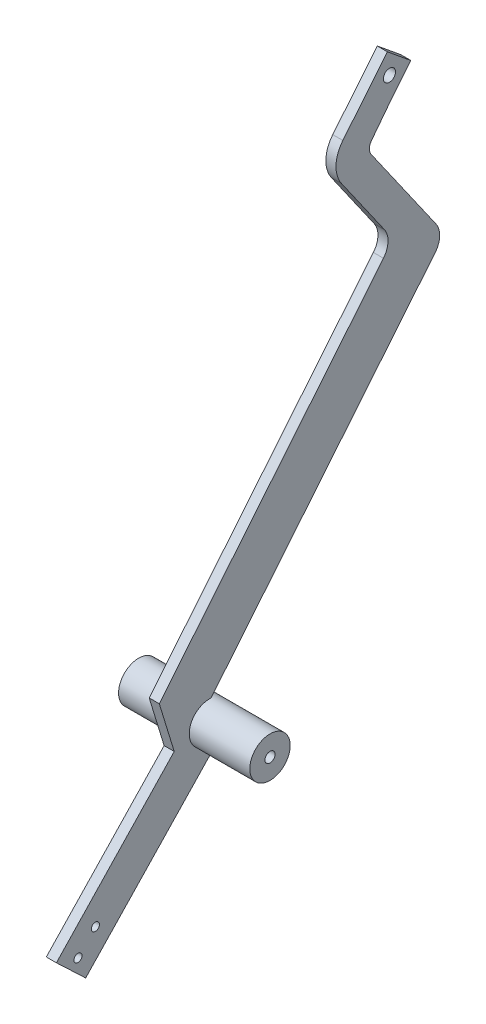
SolidWorks part; units mm, degrees
ref_plane "Front Plane" through (0, 0, 0) normal (0, 0, 1) x (1, 0, 0)
ref_plane "Top Plane" through (0, 0, 0) normal (0, 1, 0) x (1, 0, 0)
ref_plane "Right Plane" through (0, 0, 0) normal (1, 0, 0) x (0, 0, -1)
ref_plane "Plane1" through (-60.9982, 1573.0605, 105.0668) normal (1, 0, 0) x (0, 0.7736, -0.6337)
sketch "Sketch3" plane through (-60.9982, 1573.0605, 105.0668) normal (1, 0, 0) x (0, 0.7736, -0.6337)
  circle A0 centre (-394.0453, 76.3488) radius 20
  circle A1 centre (-394.0453, 76.3488) radius 5
  dimension "D1" = 40
extrude "Boss-Extrude1" add sketch "Sketch3" along normal mid plane 130
sketch "Sketch5" plane through (-60.9982, 1573.0605, 105.0668) normal (1, 0, 0) x (0, 0.7736, -0.6337)
  line L0 (-392.5842, 96.2954) -> (-591.1232, 110.8378)
  line L1 (-594.0453, 45) -> (-594.0453, 153.138) construction
  line L2 (-395.5063, 56.4022) -> (-594.0453, 70.9447)
  line L3 (-594.0453, 70.9447) -> (-591.1232, 110.8378)
  line L5 (-592.5842, 90.8913) -> (-530.6321, 86.3534) construction
  arc A0 (-392.5842, 96.2954) -> (-395.5063, 56.4022) centre (-394.0453, 76.3488) ccw
  circle A1 centre (-394.0453, 76.3488) radius 20 construction
  circle A2 centre (-582.611, 90.1608) radius 4
  circle A3 centre (-557.6778, 88.3345) radius 4
  dimension "D2" = 8
  dimension "D3" = 8
  dimension "D1" = 40
  dimension "D4" = 10
  dimension "25" = 25
extrude "Boss-Extrude2" add sketch "Sketch5" along normal mid plane 10
sketch "Sketch6" plane through (-60.9982, 1573.0605, 105.0668) normal (1, 0, 0) x (0, 0.7736, -0.6337)
  line L0 (6.218, 39.6467) -> (6.218, 202.9451) construction
  line L1 (-377.6198, 87.7595) -> (-27.2929, 87.7595)
  line L2 (-394.0453, 140.5353) -> (-43.6088, 140.5353)
  line L3 (79.2927, 22.8774) -> (79.2927, 371.7765) construction
  line L4 (64.3447, 37.2601) -> (64.3447, 317.7365) construction
  line L5 (-8.0405, 102.3427) -> (22.3027, 210.1879)
  line L6 (64.136, 218.4616) -> (94.3447, 218.4616)
  line L7 (64.3447, 248.4616) -> (94.3447, 248.4616)
  line L8 (94.3447, 218.4616) -> (94.3447, 248.4616)
  line L9 (64.136, 218.4616) -> (94.3447, 248.4616) construction
  line L10 (64.3447, 248.4616) -> (94.3447, 218.4616) construction
  line L11 (-24.3564, 155.1184) -> (-4.2481, 226.5869)
  line L12 (64.3447, 248.4616) -> (24.6306, 248.4616)
  line L13 (64.136, 218.4616) -> (31.6256, 217.4749)
  line L14 (-394.0453, 140.5353) -> (-422.0571, 98.4542)
  line L16 (-422.0571, 98.4542) -> (-387.3077, 95.1798)
  line L17 (-392.5842, 96.2954) -> (-591.1232, 110.8378) construction
  line L20 (74.2929, 233.5648) -> (84.2924, 233.4625) construction
  circle A0 centre (79.2927, 233.5136) radius 6
  arc A1 (31.6256, 217.4749) -> (22.3027, 210.1879) centre (31.929, 207.4795) ccw
  arc A2 (-4.2481, 226.5869) -> (24.6306, 248.4616) centre (24.6306, 218.4616) cw
  arc A3 (-43.6088, 140.5353) -> (-24.3564, 155.1184) centre (-43.6088, 160.5353) ccw
  arc A4 (-27.2929, 87.7595) -> (-8.0405, 102.3427) centre (-27.2929, 107.7595) ccw
  circle A5 centre (-394.0453, 76.3488) radius 20 construction
  arc A7 (-377.6198, 87.7595) -> (-387.3077, 95.1798) centre (-394.0453, 76.3488) ccw
  point P34 (79.2927, 233.5136)
  dimension "D1" = 12
  dimension "D5" = 10
  dimension "D6" = 30
  dimension "D7" = 20
  dimension "D8" = 20
  dimension "D2" = 30
  dimension "D3" = 30
  dimension "D4" = 30
extrude "Boss-Extrude3" add sketch "Sketch6" along normal mid plane 10
ref_plane "Plane2" through (0, 0, 395) normal (0, 0, -1) x (-1, 0, 0)
